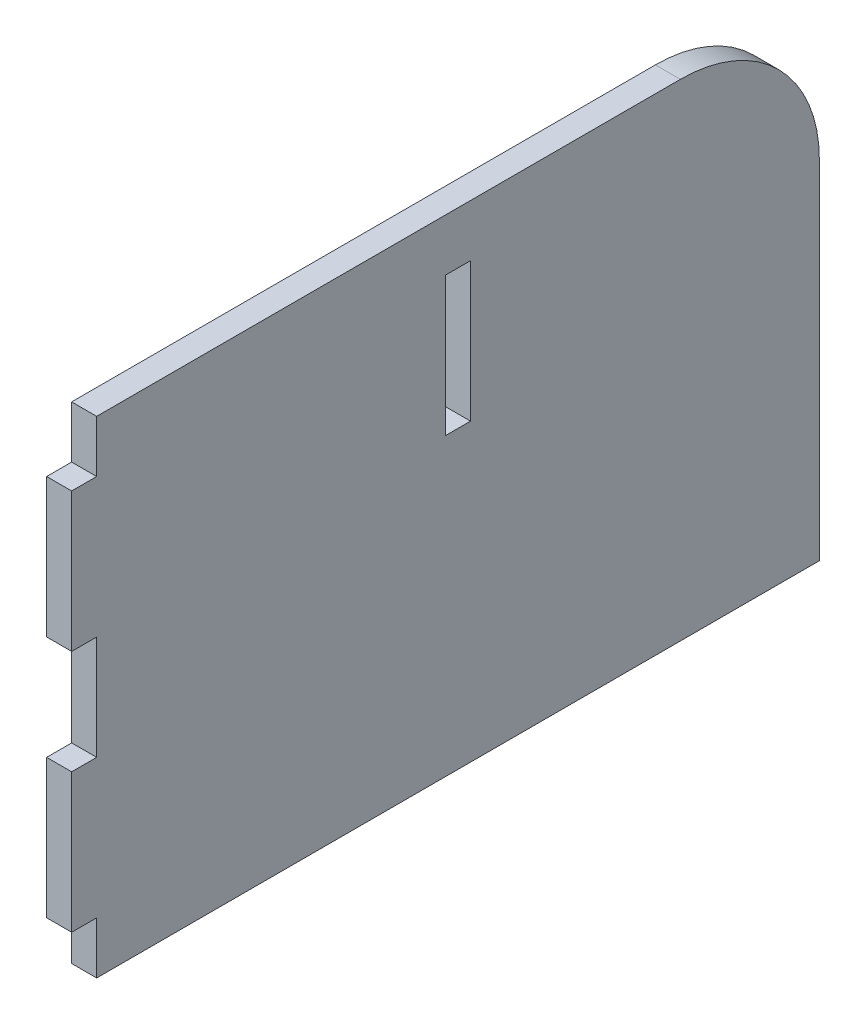
SolidWorks part; units mm, degrees
ref_plane "Front Plane" through (0, 0, 0) normal (0, 0, 1) x (1, 0, 0)
ref_plane "Top Plane" through (0, 0, 0) normal (0, 1, 0) x (1, 0, 0)
ref_plane "Right Plane" through (0, 0, 0) normal (1, 0, 0) x (0, 0, -1)
sketch "Sketch1" plane through (0, 0, 0) normal (1, 0, 0) x (0, 0, -1)
  line L0 (0, -175) -> (520, -175) construction
  line L1 (0, 0) -> (420, 0)
  line L2 (0, 0) -> (0, -37.5)
  line L3 (0, -350) -> (520, -350)
  line L4 (520, -100) -> (520, -350)
  line L5 (260, -175) -> (260, 0) construction
  line L6 (0, 0) -> (0, -37.5) construction
  line L7 (251, -37.5) -> (269, -37.5)
  line L8 (251, -37.5) -> (251, -137.5)
  line L9 (251, -137.5) -> (269, -137.5)
  line L10 (269, -37.5) -> (269, -137.5)
  line L11 (251, -37.5) -> (269, -137.5) construction
  line L12 (251, -137.5) -> (269, -37.5) construction
  line L14 (0, -137.5) -> (0, -212.5)
  line L15 (-18, -37.5) -> (0, -37.5)
  line L16 (-18, -37.5) -> (-18, -137.5)
  line L17 (-18, -137.5) -> (0, -137.5)
  line L19 (-18, -212.5) -> (0, -212.5)
  line L20 (-18, -312.5) -> (-18, -212.5)
  line L21 (0, -137.5) -> (0, -175) construction
  line L23 (-18, -312.5) -> (0, -312.5)
  line L24 (0, -312.5) -> (0, -350)
  arc A0 (520, -100) -> (420, 0) centre (420, -100) ccw
  point P7 (520, 0)
  point P10 (260, -87.5)
  point P19 (0, -87.5)
  dimension "D3" = 100
  dimension "D1" = 520
  dimension "D2" = 350
  dimension "D4" = 100
  dimension "D5" = 18
extrude "Boss-Extrude3" add sketch "Sketch1" along normal blind 18
